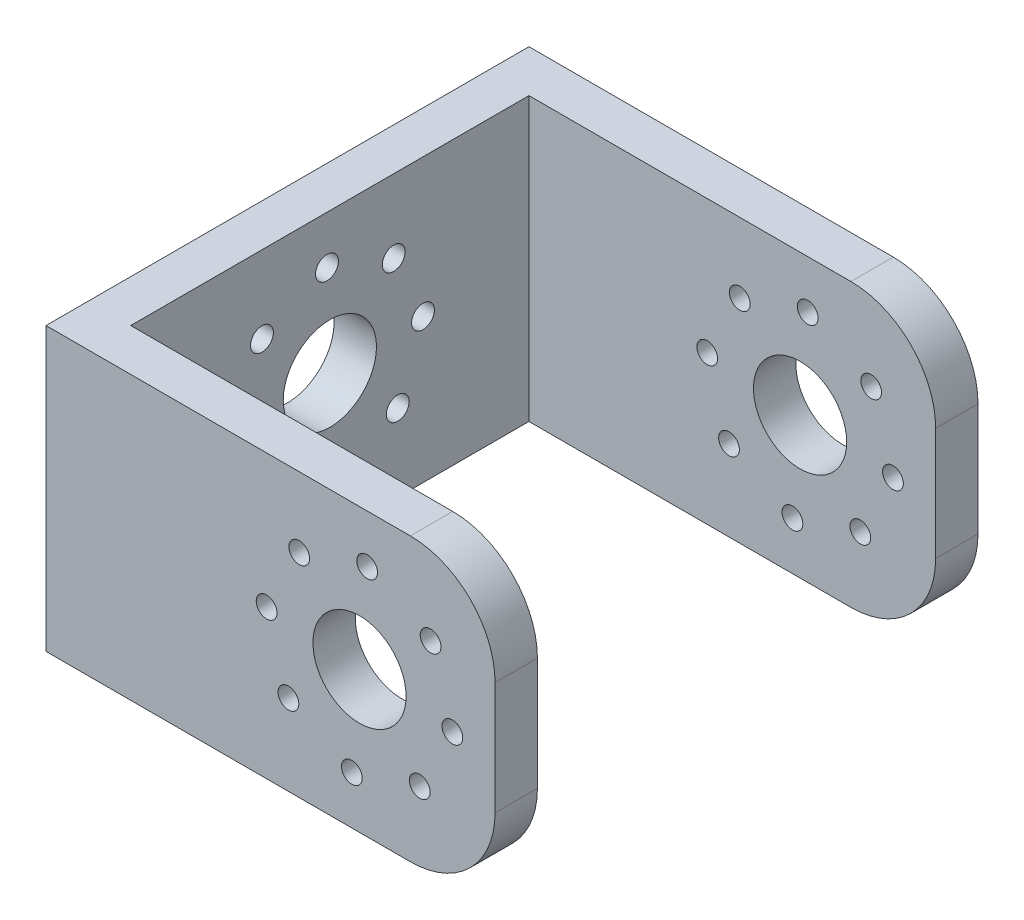
SolidWorks part; units mm, degrees
material "Aluminium 1050"
ref_plane "Front Plane" through (0, 0, 0) normal (0, 0, 1) x (1, 0, 0)
ref_plane "Top Plane" through (0, 0, 0) normal (0, 1, 0) x (1, 0, 0)
ref_plane "Right Plane" through (0, 0, 0) normal (1, 0, 0) x (0, 0, -1)
sketch "Sketch1" plane through (0, 0, 0) normal (0, 1, 0) x (1, 0, 0)
  line L0 (0, 0) -> (53, 0)
  line L1 (53, 0) -> (53, 57)
  line L2 (53, 57) -> (0, 57)
  line L3 (0, 57) -> (0, 0)
  line L4 (53, 52) -> (5, 52)
  line L5 (5, 52) -> (5, 5)
  line L6 (5, 5) -> (53, 5)
  dimension "D1" = 53
  dimension "D2" = 57
  dimension "D3" = 5
extrude "Boss-Extrude1" add sketch "Sketch1" along normal blind 33.31 contours L6 L5 L4 L1 L2 L3 L0
sketch "Sketch2" plane through (0, 0, 0) normal (0, 0, 1) x (1, 0, 0)
  line L0 (0, 33.31) -> (0, 0) construction
  line L1 (37, 33.31) -> (37, 0) construction
  circle A0 centre (37, 16.655) radius 5.5
  dimension "D2" = 11
  dimension "D1" = 37
extrude "Cut-Extrude1" cut sketch "Sketch2" against normal through all both and the other way through all
fillet "Fillet1" radius 10 4 edges at (53, 0, -54.5) (53, 0, -2.5) (53, 33.31, -54.5) (53, 33.31, -2.5)
sketch "Sketch3" plane through (0, 0, 0) normal (-1, 0, 0) x (0, 0, 1)
  line L0 (-57, 16.655) -> (0, 16.655) construction
  line L1 (-57, 33.31) -> (-57, 0) construction
  line L2 (0, 33.31) -> (0, 0) construction
  circle A0 centre (-28.5, 16.655) radius 5.5
  dimension "D1" = 11
extrude "Cut-Extrude2" cut sketch "Sketch3" against normal up to next
sketch "Sketch4" plane through (0, 0, -5) normal (0, 0, -1) x (-1, 0, 0)
  circle A0 centre (-37.9022, 27.6179) radius 1.225
  circle A1 centre (-29.886, 25.0449) radius 1.225
  circle A2 centre (-26.0371, 17.5572) radius 1.225
  circle A3 centre (-28.6101, 9.541) radius 1.225
  circle A4 centre (-36.0978, 5.6921) radius 1.225
  circle A5 centre (-44.114, 8.2651) radius 1.225
  circle A6 centre (-47.9629, 15.7528) radius 1.225
  circle A7 centre (-45.3899, 23.769) radius 1.225
extrude "Cut-Extrude3" cut sketch "Sketch4" against normal through all both and the other way through all
sketch "Sketch6" plane through (0, 0, 0) normal (-1, 0, 0) x (0, 0, 1)
  circle A0 centre (-20.9631, 8.6428) radius 1.35
  circle A1 centre (-28.8361, 5.6601) radius 1.35
  circle A2 centre (-36.5122, 9.1181) radius 1.35
  circle A3 centre (-39.4949, 16.9911) radius 1.35
  circle A4 centre (-36.0369, 24.6672) radius 1.35
  circle A5 centre (-28.1639, 27.6499) radius 1.35
  circle A6 centre (-20.4878, 24.1919) radius 1.35
  circle A7 centre (-17.5051, 16.3189) radius 1.35
extrude "Cut-Extrude4" cut sketch "Sketch6" against normal up to next and the other way through all
